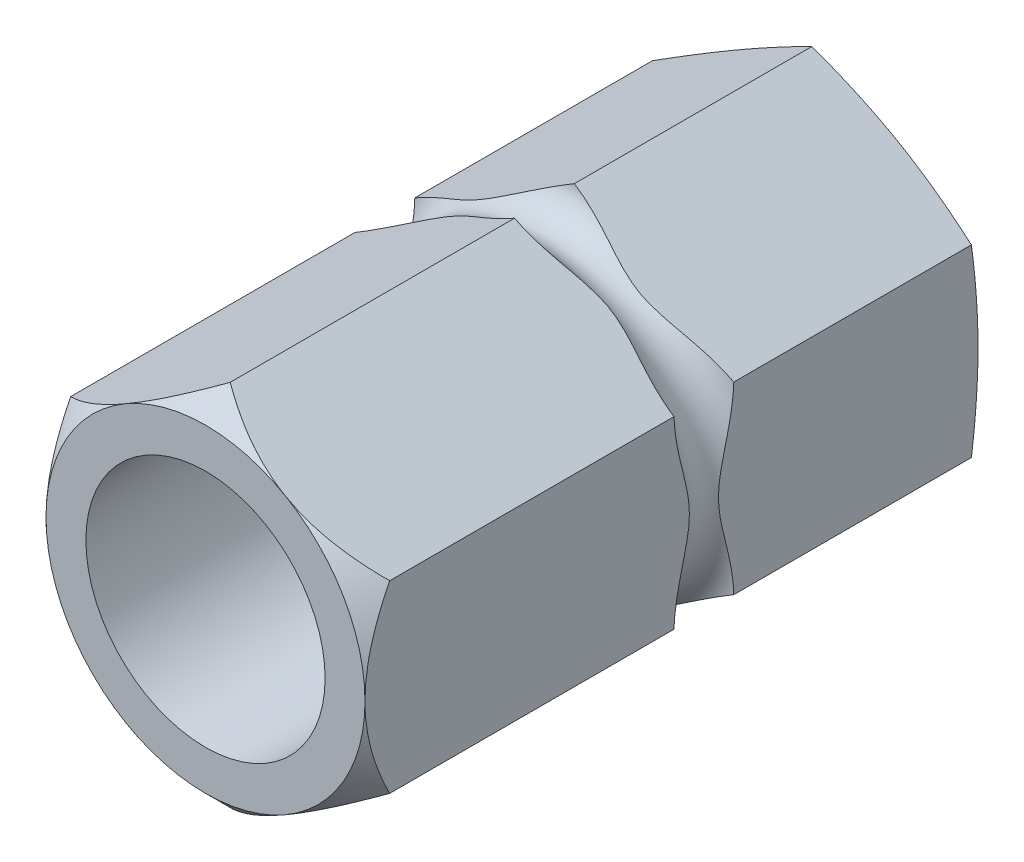
SolidWorks part; units mm, degrees
material "6061-T6 (SS)"
ref_plane "Front Plane" through (0, 0, 0) normal (0, 0, 1) x (1, 0, 0)
ref_plane "Top Plane" through (0, 0, 0) normal (0, 1, 0) x (1, 0, 0)
ref_plane "Right Plane" through (0, 0, 0) normal (1, 0, 0) x (0, 0, -1)
sketch "Sketch1" plane through (0, 0, 0) normal (0, 0, 1) x (1, 0, 0)
  line L1 (-12.7, 7.3323) -> (-12.7, -7.3323)
  line L2 (-12.7, -7.3323) -> (0, -14.6647)
  line L3 (0, -14.6647) -> (12.7, -7.3323)
  line L4 (12.7, -7.3323) -> (12.7, 7.3323)
  line L5 (12.7, 7.3323) -> (0, 14.6647)
  line L6 (0, 14.6647) -> (-12.7, 7.3323)
  circle A0 centre (0, 0) radius 9.525
  circle A1 centre (0, 0) radius 12.7 construction
  dimension "D1" = 19.05
  dimension "D2" = 25.4
extrude "Extrude1" add sketch "Sketch1" against normal blind 59
sketch "Sketch2" plane through (0, 0, 0) normal (1, 0, 0) x (0, 0, -1)
  line L0 (59, 12) -> (49, 12)
  line L1 (49, 12) -> (48.286, 14.6647)
  line L2 (59, 7.3323) -> (59, 14.6647) construction
  line L3 (59, 12) -> (59, 14.6647)
  line L4 (59, 14.6647) -> (0, 14.6647) construction
  line L5 (59, 14.6647) -> (48.286, 14.6647)
  line L6 (0, 7.3323) -> (0, 14.6647) construction
  line L7 (0, 12.7) -> (0, 14.6647)
  line L8 (0, 12.7) -> (1.9647, 14.6647)
  line L9 (1.9647, 14.6647) -> (0, 14.6647)
  line L10 (0, 0) -> (59, 0) construction
  line L11 (59, -7.3323) -> (59, 7.3323) construction
  circle A0 centre (26.9875, 14.7812) radius 2.3813
  dimension "D8" = 4.7625
  dimension "D1" = 12
  dimension "D2" = 105
  dimension "D3" = 10
  dimension "D4" = 12.7
  dimension "D5" = 45
  dimension "D6" = 26.9875
  dimension "D7" = 14.7812
revolve "Cut-Revolve3" cut sketch "Sketch2" angle 360 about L10
sketch "Sketch3" plane through (0, 0, -59) normal (0, 0, -1) x (-1, 0, 0)
  line L1 (-15.3836, -14.7482) -> (19.9987, -14.7482)
  line L2 (-15.3836, -14.7482) -> (-15.3836, 14.4807)
  line L3 (-15.3836, 14.4807) -> (19.9987, 14.4807)
  line L4 (19.9987, -14.7482) -> (19.9987, 14.4807)
extrude "Cut-Extrude1" cut sketch "Sketch3" against normal blind 10
